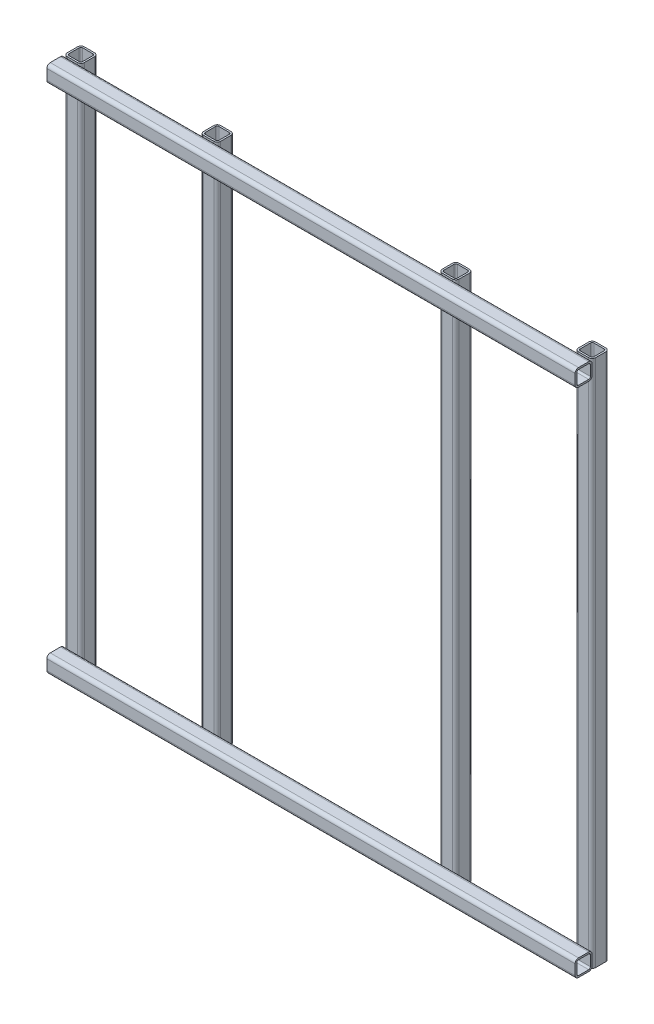
SolidWorks part; units mm, degrees
ref_plane "Front Plane" through (0, 0, 0) normal (0, 0, 1) x (1, 0, 0)
ref_plane "Top Plane" through (0, 0, 0) normal (0, 1, 0) x (1, 0, 0)
ref_plane "Right Plane" through (0, 0, 0) normal (1, 0, 0) x (0, 0, -1)
sketch3d "3DSketch1"
  line L0 (600, -610, 0) -> (600, -610, 20)
  line L1 (0, 0, 0) -> (600, 0, 0)
  line L2 (0, 0, 0) -> (0, -620, 0)
  line L3 (0, -620, 0) -> (600, -620, 0)
  line L4 (600, 0, 0) -> (600, -620, 0)
  line L5 (0, -610, 0) -> (0, -610, 20)
  line L6 (0, -10, 0) -> (0, -10, 20)
  line L7 (600, -10, 0) -> (600, -10, 20)
  line L8 (-10, -10, 20) -> (610, -10, 20)
  line L9 (600, -610, 0) -> (0, -610, 0)
  line L10 (600, -10, 0) -> (0, -10, 0)
  line L11 (-10, -610, 20) -> (610, -610, 20)
  line L12 (440, 0, 0) -> (440, -620, 0)
  line L13 (160, -620, 0) -> (160, 0, 0)
  dimension "D1" = 600
  dimension "D2" = 620
  dimension "D3" = 20
  dimension "D6" = 620
  dimension "D4" = 10
  dimension "D5" = 10
  dimension "D7" = 10
  dimension "D8" = 620
  dimension "D9" = 10
  dimension "D10" = 160
  dimension "D11" = 160
other "Square tube 20 X 20 X 2(1)"
ref_plane "Plane1" through (600, 0, 0) normal (0, -1, 0) x (1, 0, 0)
sketch "Sketch12" plane through (600, 0, 0) normal (0, -1, 0) x (1, 0, 0)
  line L0 (-6, -8) -> (6, -8)
  line L1 (-8, -6) -> (-8, 6)
  line L2 (6, 8) -> (-6, 8)
  line L3 (8, 6) -> (8, -6)
  line L4 (-6, -10) -> (6, -10)
  line L5 (-10, -6) -> (-10, 6)
  line L6 (6, 10) -> (-6, 10)
  line L7 (10, 6) -> (10, -6)
  arc A0 (10, 6) -> (6, 10) centre (6, 6) ccw
  arc A1 (6, -10) -> (10, -6) centre (6, -6) ccw
  arc A2 (-10, -6) -> (-6, -10) centre (-6, -6) ccw
  arc A3 (-6, 10) -> (-10, 6) centre (-6, 6) ccw
  arc A4 (-6, 8) -> (-8, 6) centre (-6, 6) ccw
  arc A5 (8, 6) -> (6, 8) centre (6, 6) ccw
  arc A6 (6, -8) -> (8, -6) centre (6, -6) ccw
  arc A7 (-8, -6) -> (-6, -8) centre (-6, -6) ccw
  point P0 (-10, 0)
  point P1 (10, 0)
  point P2 (0, 10)
  point P3 (0, -10)
  point P4 (0, 0)
  point P5 (-10, -10)
  point P6 (10, -10)
  point P7 (10, 10)
  point P8 (-10, 10)
  point P33 (0, 0)
  point P35 (0, 0)
  dimension "D1" = 4
  dimension "Thickness" = 2
  dimension "V_leg" = 20
